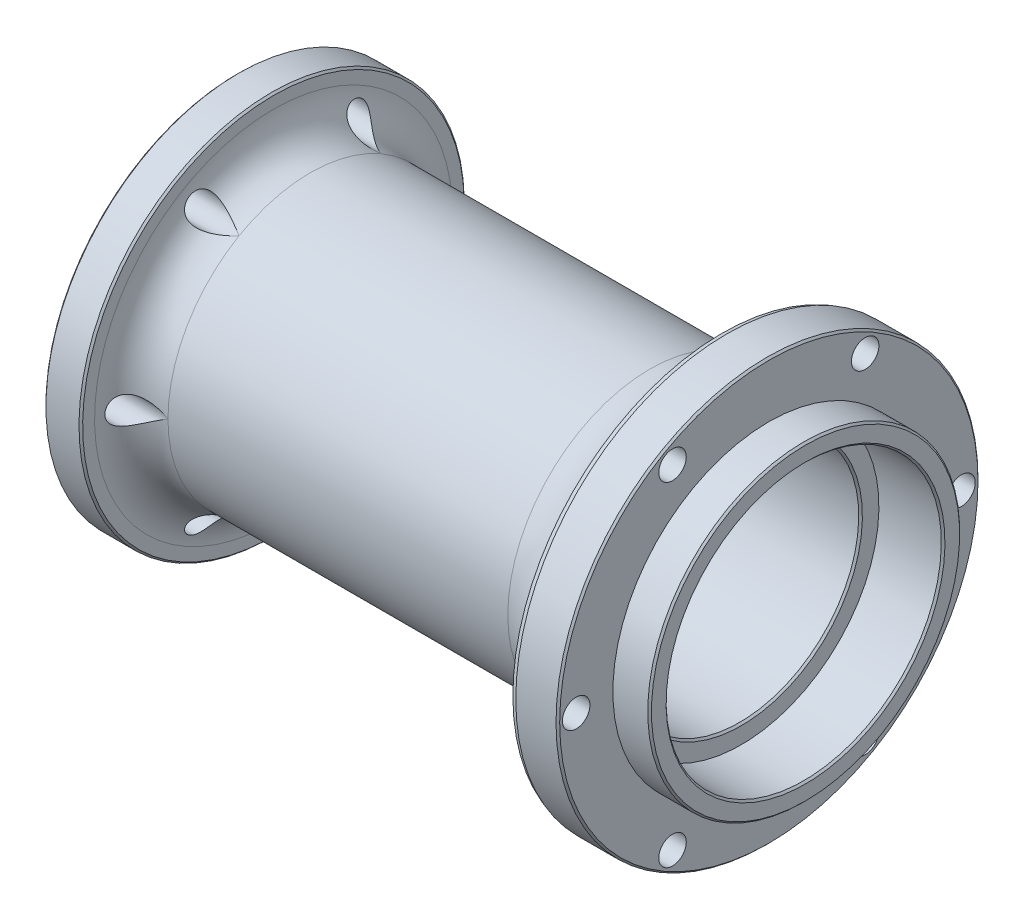
SolidWorks part; units mm, degrees
material "7079 Alloy"
ref_plane "Front Plane" through (0, 0, 0) normal (0, 0, 1) x (1, 0, 0)
ref_plane "Top Plane" through (0, 0, 0) normal (0, 1, 0) x (1, 0, 0)
ref_plane "Right Plane" through (0, 0, 0) normal (1, 0, 0) x (0, 0, -1)
sketch "Sketch1" plane through (0, 0, 0) normal (0, 0, 1) x (1, 0, 0)
  line L0 (-26.5216, 21) -> (-22.5216, 21)
  line L1 (-22.5216, 21) -> (-22.5216, 19.5)
  line L2 (-18.5216, 15.5) -> (18.5216, 15.5)
  line L3 (-26.5216, 21) -> (-26.5216, 13)
  line L4 (-26.5216, 13) -> (-18.5216, 13)
  line L5 (-18.5216, 13) -> (-18.5216, 10)
  line L6 (-18.5216, 10) -> (0.4784, 10)
  line L7 (19.6727, 0) -> (-37.8023, 0) construction
  line L8 (24.8658, 19.5417) -> (26.4784, 23)
  line L9 (26.4784, 23) -> (31.4784, 23)
  line L10 (31.4784, 23) -> (31.4784, 17)
  line L11 (31.4784, 17) -> (35.4784, 17)
  line L12 (35.4784, 17) -> (35.4784, 15)
  line L13 (28.4784, 13) -> (0.4784, 13)
  line L14 (0.4784, 13) -> (0.4784, 10)
  line L15 (35.4784, 15) -> (28.4784, 15)
  line L16 (28.4784, 15) -> (28.4784, 13)
  arc A0 (-22.5216, 19.5) -> (-18.5216, 15.5) centre (-18.5216, 19.5) ccw
  arc A1 (18.5216, 15.5) -> (24.8658, 19.5417) centre (18.5216, 22.5) ccw
  point P21 (0, 15.5)
  dimension "D6" = 4
  dimension "D16" = 7
  dimension "D1" = 26
  dimension "D2" = 8
  dimension "D3" = 31
  dimension "D4" = 42
  dimension "D5" = 4
  dimension "D7" = 20
  dimension "D8" = 4
  dimension "D9" = 58
  dimension "D10" = 34
  dimension "D11" = 26
  dimension "D12" = 35
  dimension "D13" = 46
  dimension "D14" = 30
  dimension "D15" = 7
  dimension "D17" = 25
  dimension "D18" = 5
revolve "Revolve1" add sketch "Sketch1" angle 360 about L7
chamfer "Chamfer1" distance 0.2 angle 45 10 edges at (0.4784, 10, 0) (-18.5216, 10, 0) (-26.5216, 13, 0) (-26.5216, 21, 0) (-22.5216, 21, 0) (31.4784, 23, 0) (35.4784, 17, 0) (28.4784, 13, 0) (35.4784, 15, 0) (26.4784, 23, 0)
hole_wizard "M3 Tapped Hole1" positions "Sketch3" profile "Sketch4" tap size "M3" standard "ISO"
sketch "Sketch3" plane through (-26.5216, 0, 0) normal (-1, 0, 0) x (0, 0, 1)
  point P0 (-17, 0)
  dimension "D1" = 17
sketch "Sketch4" plane through (-26.5216, 0, -17) normal (0, 1, 0) x (0, 0, 1)
  line L0 (0, 0) -> (0, 58)
  line L1 (0, 58) -> (1.5, 58)
  line L2 (1.5, 58) -> (1.5, 0)
  line L5 (1.5, 0) -> (0, 0)
  line L11 (0, -6.35) -> (0, 107.95) construction
  dimension "Thread Major Dia." = 3
  dimension "Thru Tap Drill Depth" = 58
hole_wizard "M3 Tapped Hole2" positions "Sketch6" profile "Sketch7" tap size "M3" standard "ISO"
sketch "Sketch6" plane through (31.4784, 0, 0) normal (1, 0, 0) x (0, 0, -1)
  point P0 (-21, 0)
  dimension "D1" = 21
sketch "Sketch7" plane through (31.4784, 0, 21) normal (0, 1, 0) x (0, 0, -1)
  line L0 (0, 0) -> (0, 9.2511)
  line L1 (0, 9.2511) -> (1.25, 8.5)
  line L2 (1.25, 8.5) -> (1.25, 7)
  line L3 (1.25, 7) -> (1.5, 7)
  line L4 (1.5, 7) -> (1.5, 0)
  line L5 (1.5, 0) -> (0, 0)
  line L10 (0, 9.2511) -> (-1.25, 8.5) construction
  line L11 (0, -6.35) -> (0, 107.95) construction
  dimension "Tap Drill Dia." = 2.5
  dimension "Tap Drill Depth" = 8.5
  dimension "Thread Major Dia." = 3
  dimension "Thread Depth" = 7
  dimension "Drill Angle" = 118
pattern_circular "CirPattern1" count 6 over 360 about axis through (0, 0, 0) along (1, 0, 0) of "M3 Tapped Hole1", "M3 Tapped Hole2"
